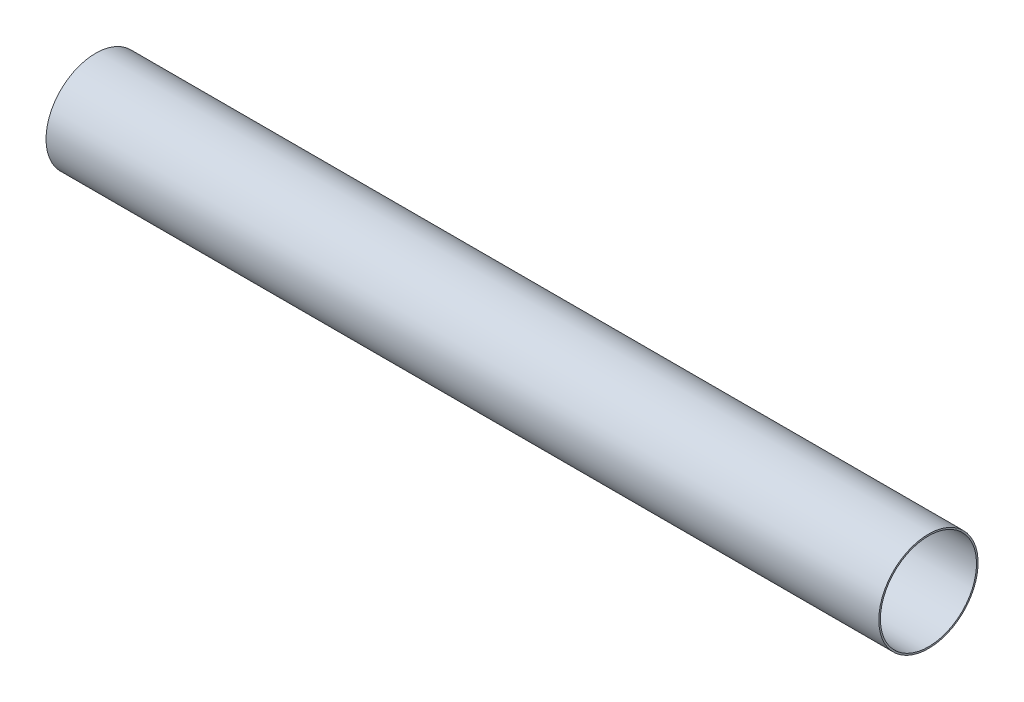
SolidWorks part; units mm, degrees
ref_plane "Plan de face" through (0, 0, 0) normal (0, 0, 1) x (1, 0, 0)
ref_plane "Plan de dessus" through (0, 0, 0) normal (0, 1, 0) x (1, 0, 0)
ref_plane "Plan de droite" through (0, 0, 0) normal (1, 0, 0) x (0, 0, -1)
sketch "Esquisse1" plane through (0, 0, 0) normal (0, 0, 1) x (1, 0, 0)
  line L0 (0, 0) -> (0, 77.47) construction
  line L1 (0, 0) -> (142.5133, 0) construction
  line L2 (0, 77.47) -> (1300, 77.47)
  line L3 (0, 77.47) -> (0, -77.47) construction
  line L4 (0, 75) -> (1300, 75)
  line L5 (1300, 77.47) -> (1300, 75)
  line L6 (0, -77.47) -> (1300, -77.47) construction
  line L7 (0, 77.47) -> (0, 75)
  dimension "D1" = 150
  dimension "D2" = 2.47
  dimension "D3" = 1300
revolve "Révolution1" add sketch "Esquisse1" angle 360 about L1
ref_plane "Plan2" through (0, 77.47, 0) normal (0, 1, 0) x (1, 0, 0)
